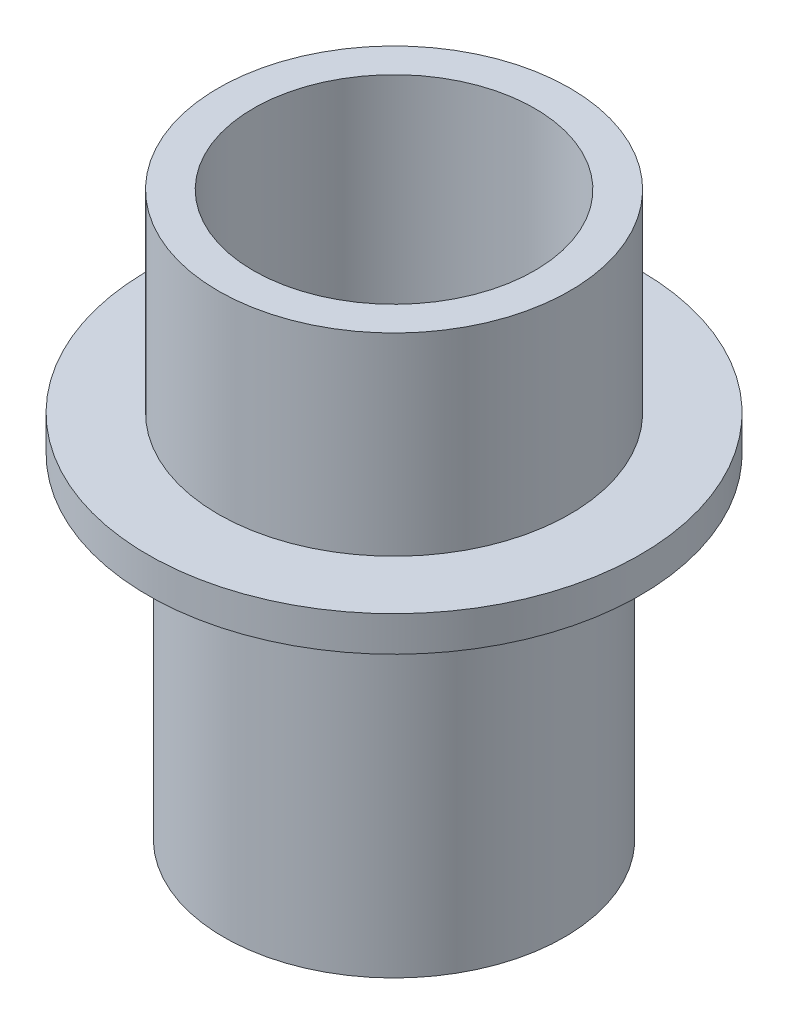
SolidWorks part; units mm, degrees
ref_plane "Front Plane" through (0, 0, 0) normal (0, 0, 1) x (1, 0, 0)
ref_plane "Top Plane" through (0, 0, 0) normal (0, 1, 0) x (1, 0, 0)
ref_plane "Right Plane" through (0, 0, 0) normal (1, 0, 0) x (0, 0, -1)
sketch "Sketch1" plane through (0, 0, 0) normal (0, 1, 0) x (1, 0, 0)
  circle A0 centre (0, 0) radius 22.225
  dimension "D1" = 44.45
extrude "Boss-Extrude1" add sketch "Sketch1" along normal blind 50.8
sketch "Sketch2" plane through (0, 0, 0) normal (0, -1, 0) x (1, 0, 0)
  circle A0 centre (0, 0) radius 22.225
  circle A1 centre (0, 0) radius 15.375
  dimension "D1" = 30.75
extrude "Cut-Extrude1" cut sketch "Sketch2" against normal blind 30.1625
sketch "Sketch3" plane through (0, 50.8, 0) normal (0, 1, 0) x (1, 0, 0)
  circle A0 centre (0, 0) radius 12.7
  dimension "D1" = 25.4
extrude "Cut-Extrude2" cut sketch "Sketch3" against normal offset from surface (49.2125 mm away) 1.5875 up to face at (0, 0, -15.375)
sketch "Sketch5" plane through (0, 50.8, 0) normal (0, 1, 0) x (1, 0, 0)
  circle A0 centre (0, 0) radius 22.225
  circle A1 centre (0, 0) radius 15.875
  dimension "D1" = 31.75
extrude "Cut-Extrude3" cut sketch "Sketch5" against normal offset from surface (17.4625 mm away) 3.175 up to face at (0, 30.1625, -15.375)
sketch "Sketch6" plane through (0, 0, 0) normal (0, -1, 0) x (1, 0, 0)
  line L0 (0, 7.0711) -> (0, -7.0711) construction
  line L1 (-7.0711, 7.0711) -> (7.0711, 7.0711) construction
  line L2 (-7.0711, 7.0711) -> (-7.0711, -7.0711) construction
  line L3 (-7.0711, -7.0711) -> (7.0711, -7.0711) construction
  line L4 (7.0711, 7.0711) -> (7.0711, -7.0711) construction
  line L5 (7.0711, 0) -> (-7.0711, 0) construction
  circle A0 centre (0, 0) radius 8.001
  circle A1 centre (-7.0711, 7.0711) radius 1.7005
  circle A2 centre (-7.1629, -6.97) radius 1.7005
  circle A3 centre (7.1586, -7.1039) radius 1.7005
  circle A4 centre (7.036, 7.1874) radius 1.7005
  dimension "D1" = 16.002
  dimension "D6" = 3.4011
  dimension "D2" = 0
  dimension "D3" = 0
  dimension "D4" = 20
extrude "MotorInterfacfe" cut sketch "Sketch6" against normal through all
